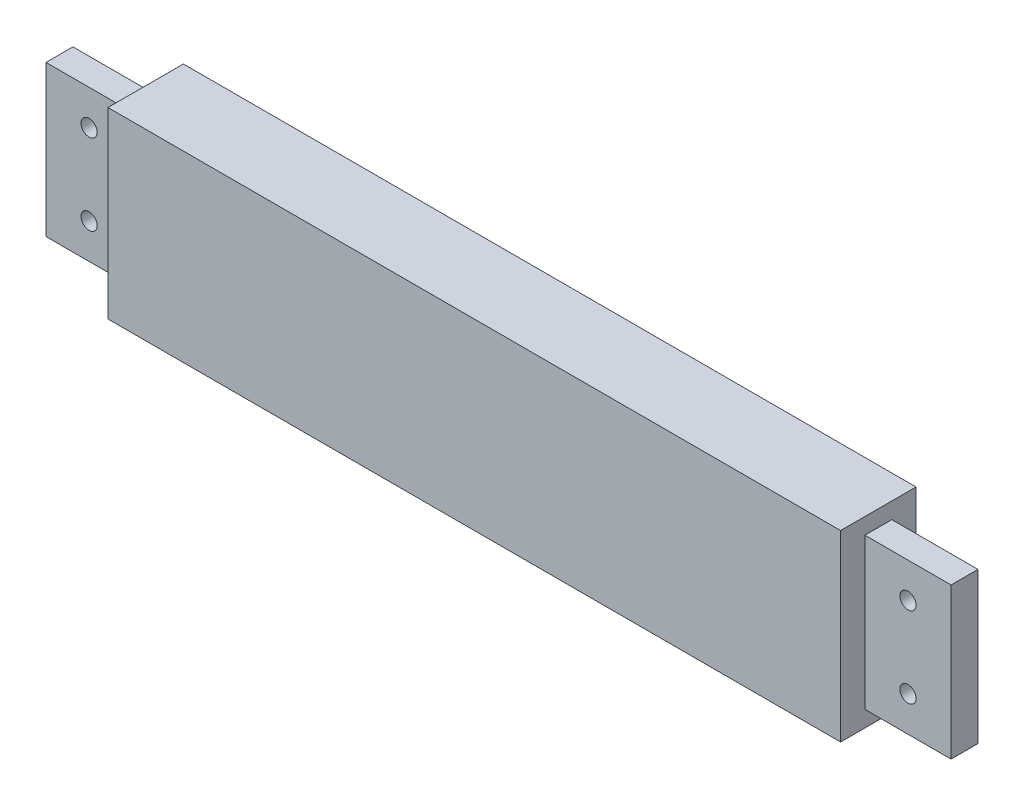
SolidWorks part; units mm, degrees
ref_plane "Front Plane" through (0, 0, 0) normal (0, 0, 1) x (1, 0, 0)
ref_plane "Top Plane" through (0, 0, 0) normal (0, 1, 0) x (1, 0, 0)
ref_plane "Right Plane" through (0, 0, 0) normal (1, 0, 0) x (0, 0, -1)
sketch "Sketch1" plane through (0, 0, 0) normal (0, 0, 1) x (1, 0, 0)
  line L1 (215.9, 53.975) -> (-215.9, 53.975)
  line L2 (215.9, 53.975) -> (215.9, -53.975)
  line L3 (215.9, -53.975) -> (-215.9, -53.975)
  line L4 (-215.9, 53.975) -> (-215.9, -53.975)
  line L5 (215.9, 53.975) -> (-215.9, -53.975) construction
  line L6 (215.9, -53.975) -> (-215.9, 53.975) construction
  point P0 (0, 0)
  dimension "D1" = 107.95
  dimension "D2" = 431.8
extrude "Boss-Extrude1" add sketch "Sketch1" along normal mid plane 44.45
sketch "Sketch2" plane through (215.9, 0, 0) normal (1, 0, 0) x (0, 0, -1)
  line L1 (7.9375, 44.45) -> (-7.9375, 44.45)
  line L2 (7.9375, 44.45) -> (7.9375, -44.45)
  line L3 (7.9375, -44.45) -> (-7.9375, -44.45)
  line L4 (-7.9375, 44.45) -> (-7.9375, -44.45)
  line L5 (7.9375, 44.45) -> (-7.9375, -44.45) construction
  line L6 (7.9375, -44.45) -> (-7.9375, 44.45) construction
  point P0 (0, 0)
  dimension "D1" = 15.875
  dimension "D2" = 88.9
extrude "Boss-Extrude2" add sketch "Sketch2" along normal blind 50.8 contours L4 L3 L2 L1
sketch "Sketch3" plane through (0, 0, 7.9375) normal (0, 0, 1) x (1, 0, 0)
  line L0 (266.7, 44.45) -> (215.9, -44.45) construction
  line L1 (241.3, 0) -> (241.3, 44.45) construction
  line L2 (266.7, 44.45) -> (215.9, 44.45) construction
  circle A0 centre (241.3, 23.8125) radius 4.7625
  circle A1 centre (241.3, -23.8125) radius 4.7625
  point P12 (0, 0)
  dimension "D1" = 9.525
  dimension "D2" = 23.8125
  dimension "D3" = 23.8125
extrude "Cut-Extrude1" cut sketch "Sketch3" against normal through all contours A0 | A1
sketch "Sketch4" plane through (215.9, 0, 0) normal (1, 0, 0) x (0, 0, -1)
  line L0 (22.225, 28.575) -> (19.05, 28.575)
  line L1 (22.225, -53.975) -> (22.225, 53.975) construction
  line L2 (19.05, 28.575) -> (19.05, 19.05)
  line L3 (19.05, 19.05) -> (22.225, 19.05)
  line L4 (-22.225, -53.975) -> (22.225, -53.975) construction
  line L5 (22.225, 28.575) -> (22.225, 19.05)
  dimension "D1" = 9.525
  dimension "D2" = 3.175
  dimension "D3" = 73.025
extrude "Cut-Extrude2" cut sketch "Sketch4" against normal through all
mirror "Mirror1" about plane through (0, 0, 0) normal (1, 0, 0) of "Boss-Extrude2", "Cut-Extrude1"
